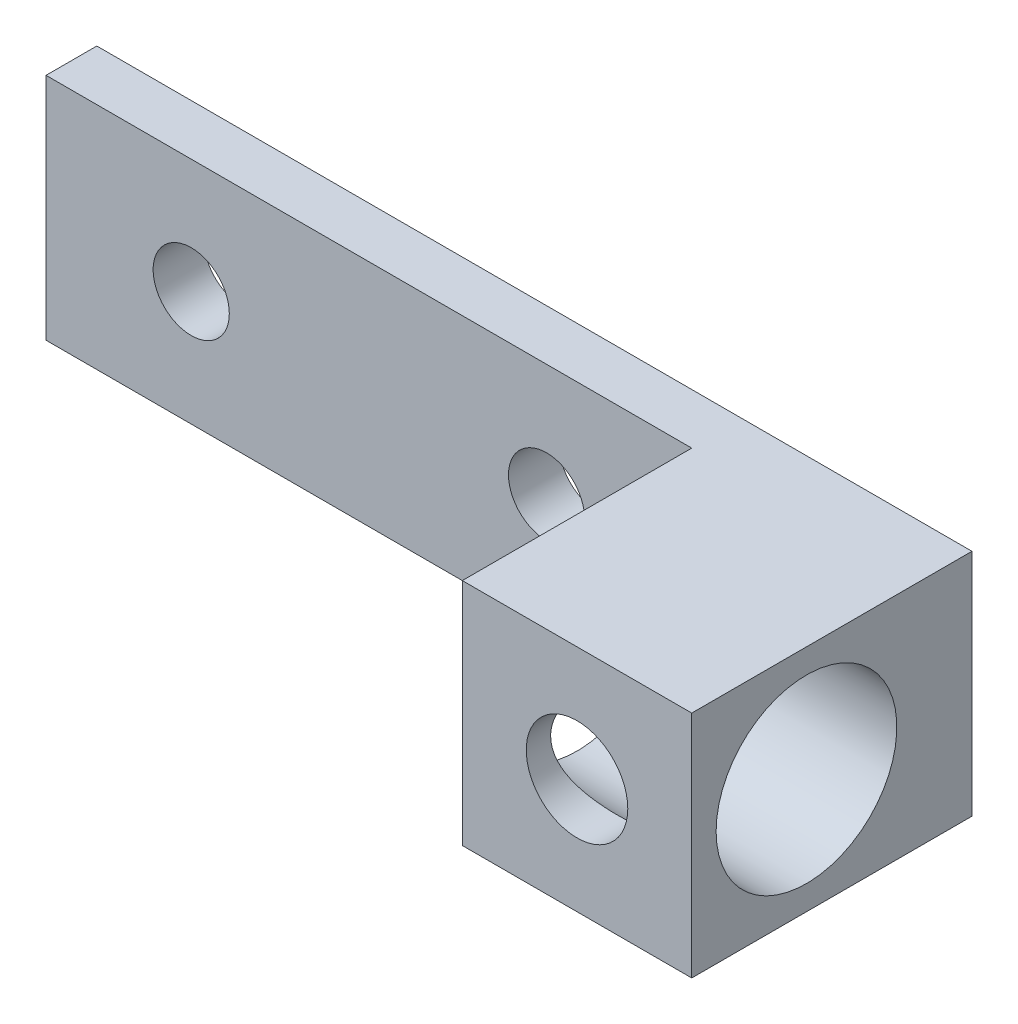
SolidWorks part; units mm, degrees
ref_plane "Front Plane" through (0, 0, 0) normal (0, 0, 1) x (1, 0, 0)
ref_plane "Top Plane" through (0, 0, 0) normal (0, 1, 0) x (1, 0, 0)
ref_plane "Right Plane" through (0, 0, 0) normal (1, 0, 0) x (0, 0, -1)
sketch "Sketch1" plane through (0, 0, 0) normal (0, 1, 0) x (1, 0, 0)
  line L0 (0, 0) -> (0, -35.052)
  line L1 (0, -35.052) -> (-28.702, -35.052)
  line L2 (-28.702, -35.052) -> (-28.702, -6.35)
  line L3 (-28.702, -6.35) -> (-109.474, -6.35)
  line L4 (-109.474, -6.35) -> (-109.474, 0)
  line L5 (-109.474, 0) -> (0, 0)
  dimension "D1" = 35.052
  dimension "D2" = 109.474
  dimension "D3" = 6.35
extrude "Extrude1" add sketch "Sketch1" along normal blind 28.702
sketch "Sketch2" plane through (-28.702, 0, 0) normal (-1, 0, 0) x (0, 0, 1)
  line L0 (35.052, 14.351) -> (7.9995, 14.351) construction
  line L1 (35.052, 28.702) -> (35.052, 0) construction
  line L2 (20.701, 0) -> (20.701, 34.4997) construction
  line L3 (6.35, 0) -> (35.052, 0) construction
  circle A0 centre (20.701, 14.351) radius 11.303
  dimension "D1" = 22.606
extrude "Extrude2" cut sketch "Sketch2" against normal through all
sketch "Sketch3" plane through (0, 0, 35.052) normal (0, 0, 1) x (1, 0, 0)
  line L0 (-14.351, 28.702) -> (-14.351, 0) construction
  line L1 (-28.702, 28.702) -> (0, 28.702) construction
  line L2 (-28.702, 0) -> (0, 0) construction
  circle A0 centre (-14.351, 14.351) radius 6.35
  dimension "D1" = 12.7
extrude "Extrude3" cut sketch "Sketch3" against normal blind 12.7
sketch "Sketch4" plane through (0, 0, 6.35) normal (0, 0, 1) x (1, 0, 0)
  line L0 (-109.474, 14.351) -> (-28.702, 14.351) construction
  line L1 (-109.474, 28.702) -> (-109.474, 0) construction
  line L2 (-28.702, 28.702) -> (-28.702, 0) construction
  line L3 (-69.088, 0) -> (-69.088, 28.702) construction
  line L4 (-109.474, 0) -> (-28.702, 0) construction
  line L5 (-109.474, 28.702) -> (-28.702, 28.702) construction
  circle A0 centre (-91.313, 14.351) radius 4.7625
  circle A1 centre (-46.863, 14.351) radius 4.7625
  point P16 (-69.088, 14.351)
  dimension "D1" = 9.525
  dimension "D2" = 44.45
extrude "Extrude4" cut sketch "Sketch4" against normal through all
